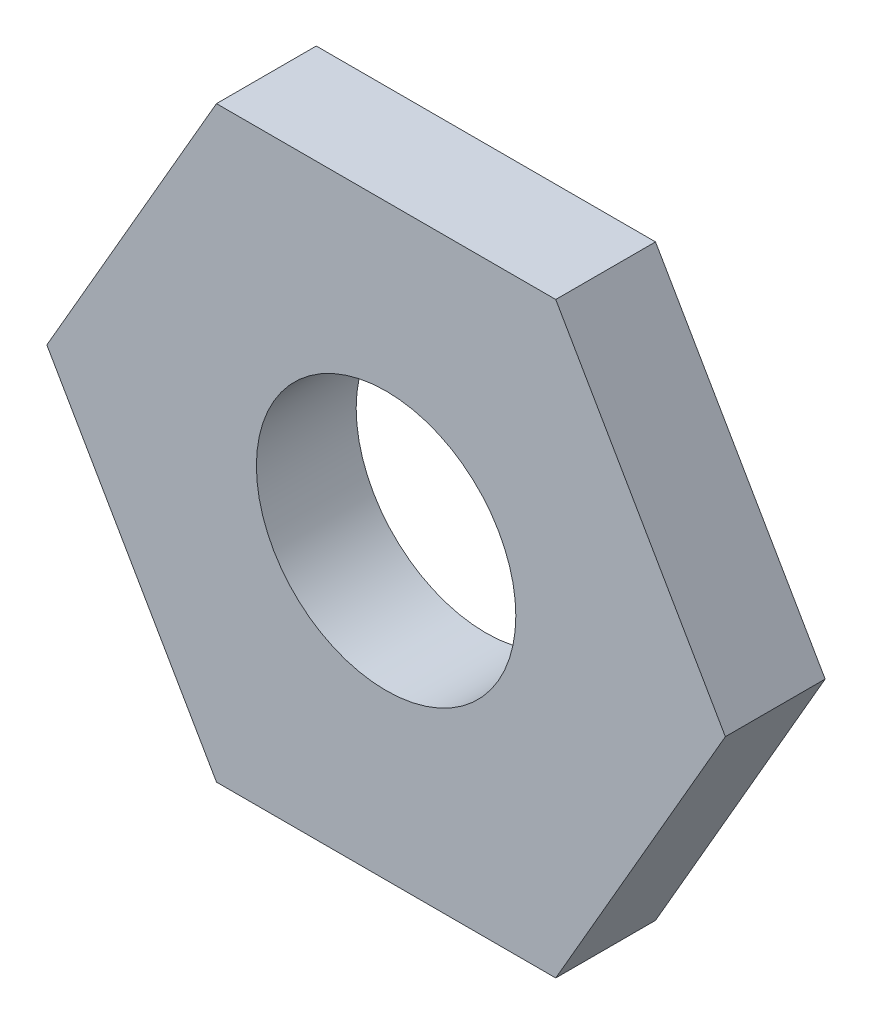
SolidWorks part; units mm, degrees
ref_plane "Front Plane" through (0, 0, 0) normal (0, 0, 1) x (1, 0, 0)
ref_plane "Top Plane" through (0, 0, 0) normal (0, 1, 0) x (1, 0, 0)
ref_plane "Right Plane" through (0, 0, 0) normal (1, 0, 0) x (0, 0, -1)
sketch "Sketch1" plane through (0, 0, 0) normal (0, 0, 1) x (1, 0, 0)
  line L0 (0, 0) -> (85.0357, 0) construction
  line L1 (-8.5, 14.7224) -> (-17, 0)
  line L2 (-17, 0) -> (-8.5, -14.7224)
  line L3 (-8.5, -14.7224) -> (8.5, -14.7224)
  line L4 (8.5, -14.7224) -> (17, 0)
  line L5 (17, 0) -> (8.5, 14.7224)
  line L6 (8.5, 14.7224) -> (-8.5, 14.7224)
  circle A0 centre (0, 0) radius 14.7224 construction
  dimension "D1" = 17
extrude "Boss-Extrude1" add sketch "Sketch1" along normal blind 5
sketch "Sketch2" plane through (0, 0, 5) normal (0, 0, 1) x (1, 0, 0)
  circle A0 centre (0, 0) radius 6.5
  dimension "D1" = 13
extrude "Cut-Extrude1" cut sketch "Sketch2" against normal through all contours A0
